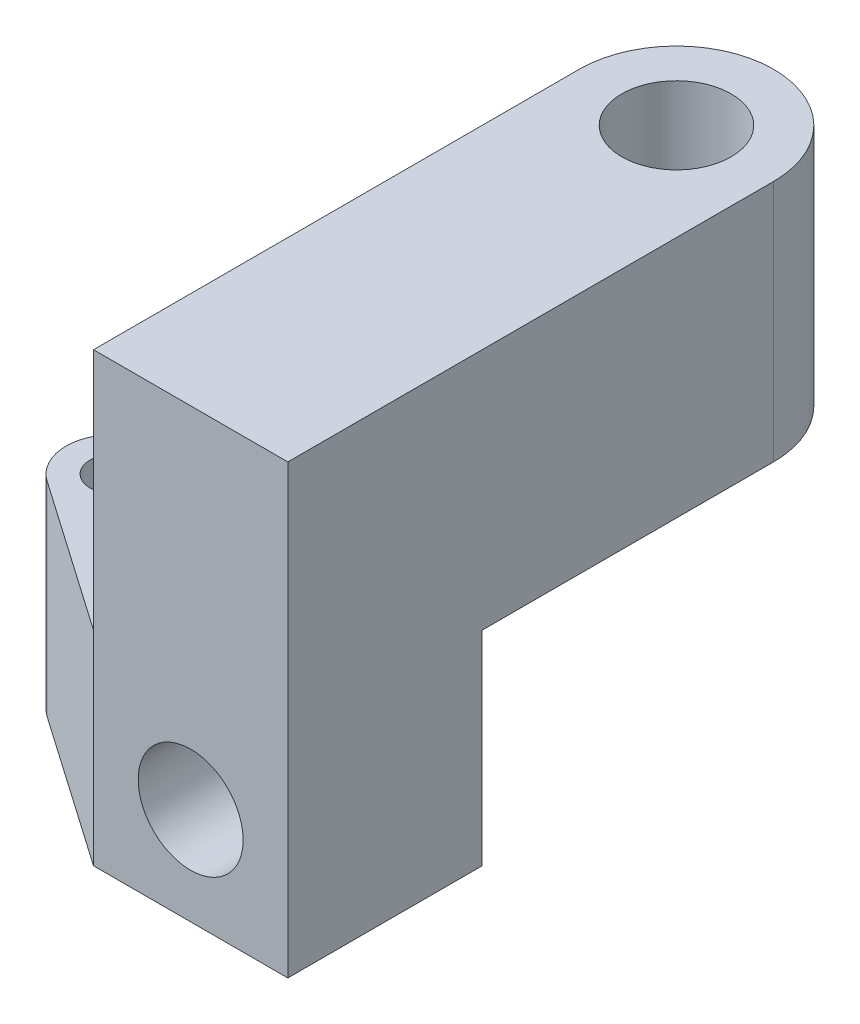
SolidWorks part; units mm, degrees
ref_plane "Front Plane" through (0, 0, 0) normal (0, 0, 1) x (1, 0, 0)
ref_plane "Top Plane" through (0, 0, 0) normal (0, 1, 0) x (1, 0, 0)
ref_plane "Right Plane" through (0, 0, 0) normal (1, 0, 0) x (0, 0, -1)
sketch "Sketch6" plane through (0, 0, 0) normal (0, 1, 0) x (1, 0, 0)
  line L0 (0, 16.9333) -> (0, 10.5833) construction
  line L1 (-6.35, -21.1667) -> (6.35, -21.1667)
  line L2 (-6.35, -21.1667) -> (-6.35, 10.5833)
  line L4 (6.35, -21.1667) -> (6.35, 10.5833)
  line L5 (-6.35, -21.1667) -> (4.5146, 15.0488) construction
  line L6 (-4.5146, 15.0488) -> (6.35, -21.1667) construction
  arc A0 (6.35, 10.5833) -> (-6.35, 10.5833) centre (0, 10.5833) ccw
  circle A1 centre (0, 10.5833) radius 3.175
  point P0 (0, 0)
  dimension "D1" = 31.75
  dimension "D2" = 6.35
  dimension "D3" = 6.35
extrude "Boss-Extrude4" add sketch "Sketch6" along normal blind 25.4 contours A0 L2 L1 L4
sketch "Sketch7" plane through (0, 0, 0) normal (0, -1, 0) x (1, 0, 0)
  circle A0 centre (0, -10.5833) radius 3.175
extrude "Cut-Extrude1" cut sketch "Sketch7" against normal up to next
ref_plane "Plane2" through (0, 0, -16.9333) normal (0, 0, 1) x (1, 0, 0)
sketch "Sketch9" plane through (0, 0, -16.9333) normal (0, 0, 1) x (1, 0, 0)
  line L1 (7.1567, 0) -> (-6.9125, 0)
  line L2 (7.1567, 0) -> (7.1567, 9.525)
  line L3 (7.1567, 9.525) -> (-6.9125, 9.525)
  line L4 (-6.9125, 0) -> (-6.9125, 9.525)
extrude "Cut-Extrude2" cut sketch "Sketch9" along normal blind 25.4
sketch "Sketch10" plane through (6.35, 0, 0) normal (1, 0, 0) x (0, 0, -1)
  line L1 (-21.1667, 0) -> (-8.4667, 0)
  line L2 (-21.1667, 0) -> (-21.1667, 9.525)
  line L3 (-21.1667, 9.525) -> (-8.4667, 9.525)
  line L4 (-8.4667, 0) -> (-8.4667, 9.525)
extrude "Boss-Extrude5" add sketch "Sketch10" along normal blind 12.7
sketch "Sketch11" plane through (0, 9.525, 0) normal (0, 1, 0) x (1, 0, 0)
  line L0 (19.05, -8.4667) -> (19.05, -11.6417) construction
  line L1 (19.05, -8.4667) -> (19.05, -21.1667) construction
  line L2 (19.05, -11.6417) -> (15.875, -11.6417) construction
  line L3 (6.35, -21.1667) -> (15.9808, -8.4684)
  line L4 (15.875, -8.4667) -> (6.35, -8.4667)
  line L5 (6.35, -8.4667) -> (19.05, -8.4667)
  line L6 (19.05, -8.4667) -> (19.05, -21.1667)
  line L7 (19.05, -21.1667) -> (6.35, -21.1667)
  arc A0 (12.8478, -12.5992) -> (15.875, -8.4667) centre (15.875, -11.6417) ccw
  circle A1 centre (15.875, -11.6417) radius 1.5875
  line M4 (6.35, -21.1667) -> (19.05, -21.1667)
  line M5 (19.05, -21.1667) -> (19.05, -8.4667)
  line M6 (19.05, -8.4667) -> (6.35, -8.4667)
extrude "Cut-Extrude3" cut sketch "Sketch11" against normal blind 12.7 contours A0 L6 M6 | A0 L3 M4 M5 | A1
sketch "Sketch13" plane through (0, 9.525, 0) normal (0, 1, 0) x (1, 0, 0)
  line L1 (6.35, -21.1667) -> (19.5641, -21.1667)
  line L2 (6.35, -21.1667) -> (6.35, 0)
  line L3 (6.35, 0) -> (19.5641, 0)
  line L4 (19.5641, -21.1667) -> (19.5641, 0)
extrude "Cut-Extrude5" cut sketch "Sketch13" against normal blind 9.525
sketch "Sketch14" plane through (-6.35, 0, 0) normal (-1, 0, 0) x (0, 0, 1)
  line L0 (21.1667, 25.4) -> (21.1667, 0) construction
  line L1 (8.4667, 0) -> (21.1667, 0)
  line L2 (8.4667, 0) -> (8.4667, 9.525)
  line L3 (8.4667, 9.525) -> (21.1667, 9.525)
  line L4 (21.1667, 0) -> (21.1667, 9.525)
extrude "Boss-Extrude6" add sketch "Sketch14" along normal blind 12.7
sketch "Sketch15" plane through (0, 9.525, 0) normal (0, 1, 0) x (1, 0, 0)
  line L0 (-19.05, -8.4667) -> (-14.506, -8.4667) construction
  line L1 (-19.05, -8.4667) -> (-6.35, -8.4667) construction
  line L2 (-14.506, -8.4667) -> (-14.506, -11.6417) construction
  line L4 (-14.506, -8.4667) -> (-6.35, -8.4667)
  line L5 (-6.35, -8.4667) -> (-19.05, -8.4667)
  line L6 (-19.05, -8.4667) -> (-19.05, -21.1667)
  line L7 (-19.05, -21.1667) -> (-6.35, -21.1667)
extrude "Cut-Extrude7" cut sketch "Sketch15" against normal blind 12.7
sketch "Sketch16" plane through (0, 9.525, 0) normal (0, 1, 0) x (1, 0, 0)
  line L0 (-6.35, -21.1667) -> (-17.681, -21.1667)
  line L1 (-13.3038, -8.4667) -> (-17.681, -8.4667)
  line L2 (-14.506, -8.4667) -> (-6.35, -8.4667) construction
  line L3 (-17.681, -8.4667) -> (-6.35, -8.4667)
  line L4 (-17.681, -11.6417) -> (-17.681, -8.4667)
  line L5 (-17.681, -8.4667) -> (-17.681, -21.1667)
  line L6 (-6.35, -8.4667) -> (-6.35, -21.1667)
  arc A0 (-14.506, -8.4667) -> (-16.3163, -14.2501) centre (-14.506, -11.6417) ccw construction
extrude "Boss-Extrude7" add sketch "Sketch16" against normal blind 9.525
sketch "Sketch17" plane through (0, 9.525, 0) normal (0, -1, 0) x (1, 0, 0)
  circle A0 centre (0, -10.5833) radius 3.175
extrude "Boss-Extrude8" add sketch "Sketch17" against normal blind 15.875
sketch "Sketch18" plane through (0, 9.525, 0) normal (0, -1, 0) x (1, 0, 0)
  circle A0 centre (0, -10.5833) radius 3.5719
  dimension "D1" = 7.1437
extrude "Cut-Extrude8" cut sketch "Sketch18" against normal blind 15.875
sketch "Sketch19" plane through (0, 9.525, 0) normal (0, 1, 0) x (1, 0, 0)
  line L0 (-17.681, -8.4667) -> (-14.506, -8.4667)
  line L1 (-17.681, -8.4667) -> (-6.35, -8.4667) construction
  line L2 (-14.506, -8.4667) -> (-14.506, -8.4794)
  line L3 (-6.35, -21.1667) -> (-16.3118, -14.2377)
  line L4 (-6.35, -21.1667) -> (-17.681, -21.1667)
  line L5 (-17.681, -21.1667) -> (-17.681, -8.4667)
  circle A0 centre (-14.506, -11.6417) radius 1.5875
  arc A1 (-14.506, -8.4794) -> (-16.3118, -14.2377) centre (-14.506, -11.6417) ccw
extrude "Cut-Extrude9" cut sketch "Sketch19" against normal blind 15.875
sketch "Sketch20" plane through (0, 0, 0) normal (0, -1, 0) x (1, 0, 0)
  line L0 (-6.35, 21.1667) -> (6.35, 21.1667)
  line L1 (6.35, 21.1667) -> (6.35, 8.4667)
  line L2 (6.35, 8.4667) -> (-14.506, 8.4794)
  line L3 (-6.35, 21.1667) -> (-16.3118, 14.2377)
  arc A0 (-16.3118, 14.2377) -> (-14.506, 8.4794) centre (-14.506, 11.6417) ccw
  circle A1 centre (-14.506, 11.6417) radius 1.5875
extrude "Boss-Extrude9" add sketch "Sketch20" along normal blind 3.81
sketch "Sketch21" plane through (0, 0, 21.1667) normal (0, 0, 1) x (1, 0, 0)
  line L0 (0, -3.81) -> (0, 2.54)
  line L1 (6.35, -3.81) -> (-6.35, -3.81) construction
  circle A0 centre (0, 2.54) radius 3.429
extrude "Cut-Extrude10" cut sketch "Sketch21" against normal blind 12.7
